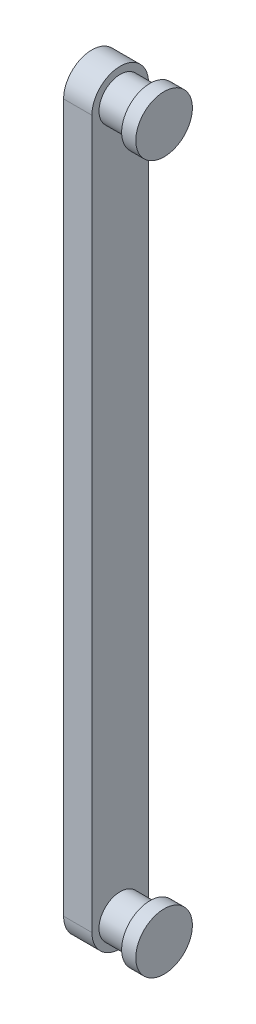
SolidWorks part; units mm, degrees
ref_plane "Plan de face" through (0, 0, 0) normal (0, 0, 1) x (1, 0, 0)
ref_plane "Plan de dessus" through (0, 0, 0) normal (0, 1, 0) x (1, 0, 0)
ref_plane "Plan de droite" through (0, 0, 0) normal (1, 0, 0) x (0, 0, -1)
sketch "Esquisse1" plane through (0, 0, 0) normal (1, 0, 0) x (0, 0, -1)
  line L0 (-4.3717, 54.6457) -> (-2, 25) construction
  line L1 (4.965, 0) -> (-4.3022, 0) construction
  line L2 (2, 25) -> (2, -25)
  line L4 (-2, 25) -> (-2, -25)
  line L5 (2, 25) -> (4.7655, 59.569) construction
  line L6 (2, -25) -> (0, 0) construction
  line L7 (0, 0) -> (-2, -25) construction
  arc A0 (2, 25) -> (-2, 25) centre (0, 25) ccw
  arc A1 (2, -25) -> (-2, -25) centre (0, -25) cw
  point P0 (0, 0)
  point P6 (0, 40)
  dimension "D1" = 4
  dimension "D2" = 50
extrude "BASE" add sketch "Esquisse1" along normal blind 2
sketch "Esquisse2" plane through (2, 0, 0) normal (1, 0, 0) x (0, 0, -1)
  line L0 (-2, 25) -> (2, 25) construction
  line L1 (2, 25) -> (0, 27) construction
  line L2 (0, 27) -> (0, 39.6014) construction
  arc A0 (2, 25) -> (-2, 25) centre (0, 25) ccw construction
  circle A1 centre (0, 25) radius 1.5
  dimension "D1" = 3
extrude "BOSS FIX" add sketch "Esquisse2" along normal blind 2.1
sketch "Esquisse3" plane through (4.1, 0, 0) normal (1, 0, 0) x (0, 0, -1)
  circle A0 centre (0, 25) radius 2
  dimension "D1" = 4
extrude "BOSS BLOCAGE" add sketch "Esquisse3" along normal blind 1
mirror "SYM FIXATION" about plane through (0, 0, 0) normal (0, 1, 0) of "BOSS BLOCAGE", "BOSS FIX"
